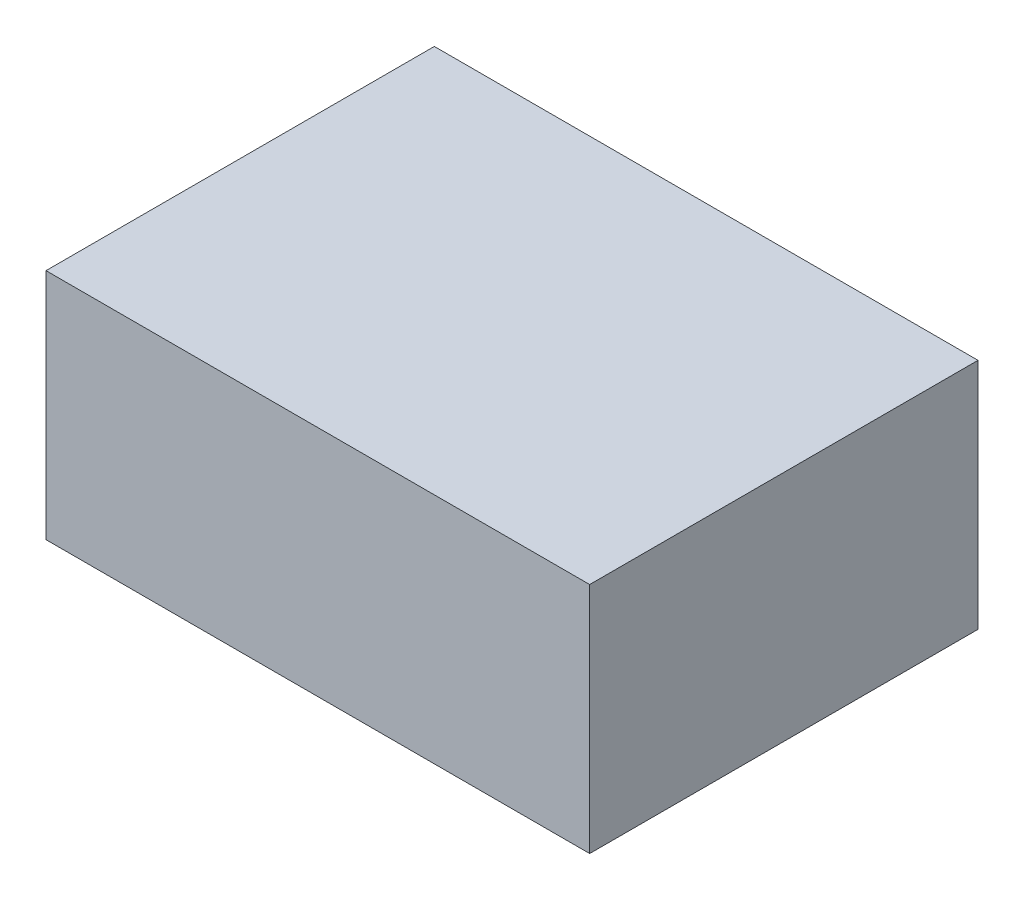
SolidWorks part; units mm, degrees
ref_plane "Front Plane" through (0, 0, 0) normal (0, 0, 1) x (1, 0, 0)
ref_plane "Top Plane" through (0, 0, 0) normal (0, 1, 0) x (1, 0, 0)
ref_plane "Right Plane" through (0, 0, 0) normal (1, 0, 0) x (0, 0, -1)
sketch "Sketch1" plane through (0, 0, 0) normal (0, 1, 0) x (1, 0, 0)
  line L1 (0, 0) -> (140, 0)
  line L2 (0, 0) -> (0, 100)
  line L3 (0, 100) -> (140, 100)
  line L4 (140, 0) -> (140, 100)
  dimension "D1" = 140
  dimension "D2" = 100
extrude "Boss-Extrude1" add sketch "Sketch1" along normal blind 60
